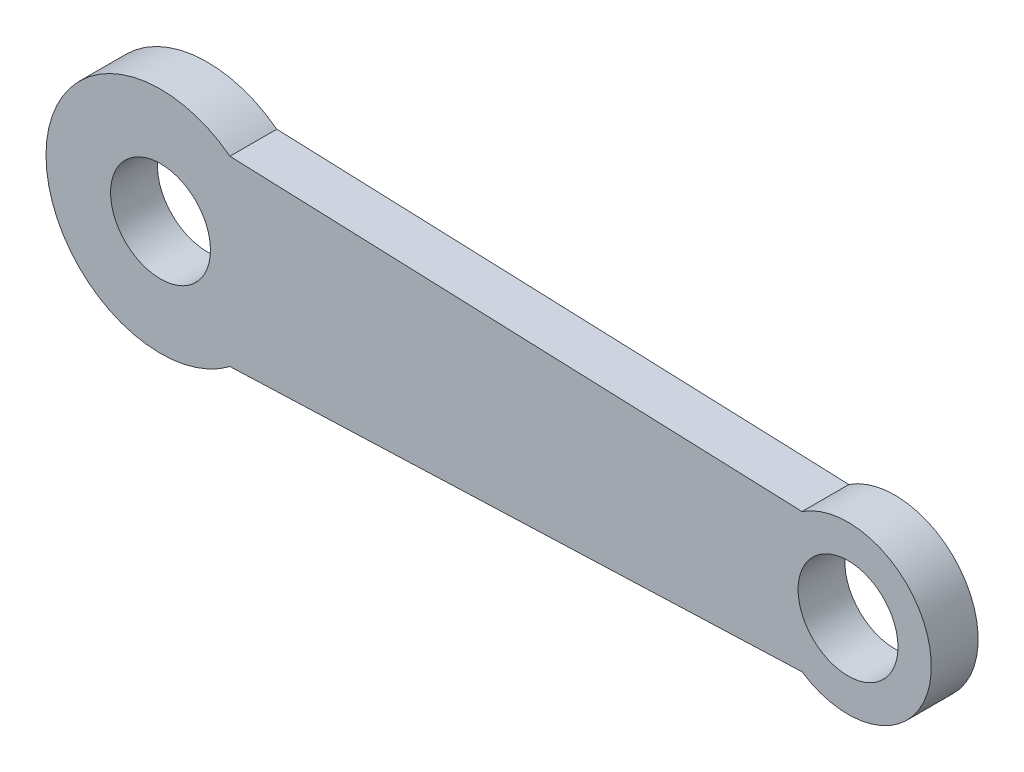
SolidWorks part; units mm, degrees
material "Plain Carbon Steel"
ref_plane "Front Plane" through (0, 0, 0) normal (0, 0, 1) x (1, 0, 0)
ref_plane "Top Plane" through (0, 0, 0) normal (0, 1, 0) x (1, 0, 0)
ref_plane "Right Plane" through (0, 0, 0) normal (1, 0, 0) x (0, 0, -1)
sketch "Sketch1" plane through (0, 0, 0) normal (0, 0, 1) x (1, 0, 0)
  circle A0 centre (0, 0) radius 11
  dimension "D1" = 22
extrude "Boss-Extrude1" add sketch "Sketch1" along normal mid plane 4.5
sketch "Sketch2" plane through (0, 0, 0) normal (0, 0, 1) x (1, 0, 0)
  circle A0 centre (66.0482, 0) radius 8
  dimension "D2" = 16
  dimension "D1" = 66.0482
extrude "Boss-Extrude2" add sketch "Sketch2" along normal mid plane 4.5
sketch "Sketch3" plane through (0, 0, 0) normal (0, 0, 1) x (1, 0, 0)
  line L0 (0, -9) -> (66.0482, -6.5)
  line L1 (66.0482, -6.5) -> (66.0482, 6.5)
  line L2 (66.0482, 6.5) -> (0, 9)
  line L3 (0, 9) -> (0, -9)
  dimension "D1" = 9
  dimension "D2" = 66.0482
  dimension "D3" = 2.5
  dimension "D4" = 13
  dimension "D5" = 66.0482
  dimension "D6" = 2.5
extrude "Boss-Extrude3" add sketch "Sketch3" along normal mid plane 4.5
sketch "Sketch4" plane through (0, 0, 0) normal (0, 0, 1) x (1, 0, 0)
  circle A0 centre (0, 0) radius 4.8
  circle A1 centre (66.0482, 0) radius 4.8
  dimension "D1" = 9.6
  dimension "D3" = 9.6
  dimension "D2" = 66.0482
extrude "Cut-Extrude1" cut sketch "Sketch4" against normal mid plane 9
